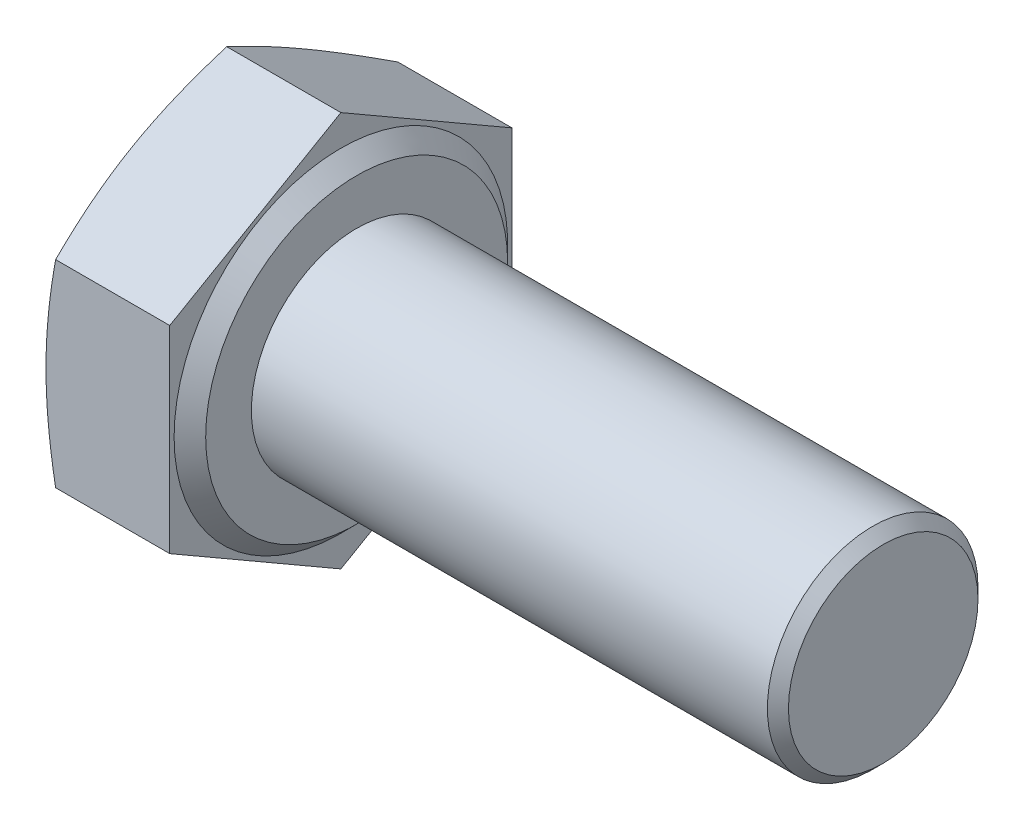
SolidWorks part; units mm, degrees
material "304 Stainless Steel"
ref_plane "Front" through (0, 0, 0) normal (0, 0, 1) x (1, 0, 0)
ref_plane "Top" through (0, 0, 0) normal (0, 1, 0) x (1, 0, 0)
ref_plane "Right" through (0, 0, 0) normal (1, 0, 0) x (0, 0, -1)
sketch "Sketch2" plane through (0, 0, 0) normal (1, 0, 0) x (0, 0, -1)
  line L1 (0, -7.5056) -> (6.5, -3.7528)
  line L2 (6.5, -3.7528) -> (6.5, 3.7528)
  line L3 (6.5, 3.7528) -> (0, 7.5056)
  line L4 (0, 7.5056) -> (-6.5, 3.7528)
  line L5 (-6.5, 3.7528) -> (-6.5, -3.7528)
  line L6 (-6.5, -3.7528) -> (0, -7.5056)
  circle A0 centre (0, 0) radius 6.5 construction
  dimension "s" = 13
extrude "BaseHead" add sketch "Sketch2" along normal blind 5.3
sketch "Sketch3" plane through (0, 0, 0) normal (0, 0, 1) x (1, 0, 0)
  line L0 (5.3, 7.5056) -> (5.3, 5.735)
  line L2 (5.3, 5.735) -> (4.7, 6.335)
  line L3 (4.7, 6.335) -> (4.7, 7.5056)
  line L5 (4.7, 7.5056) -> (5.3, 7.5056)
  line L6 (-0.9571, 0) -> (7.6478, 0) construction
  line L7 (5.3, 7.5056) -> (0, 7.5056) construction
  dimension "D1" = 45
  dimension "c" = 0.6
  dimension "dw" = 11.47
revolve "BearingFace" cut sketch "Sketch3" angle 360 about L6
sketch "Sketch4" plane through (0, 0, 0) normal (0, 0, 1) x (1, 0, 0)
  line L0 (-0.4935, 0) -> (3.5626, 0) construction
  line L2 (0, 7.5056) -> (0.366, 7.5056)
  line L4 (0.366, 7.5056) -> (0, 6.5)
  line L6 (0, 6.5) -> (0, 7.5056)
  line L7 (4.7, 7.5056) -> (0, 7.5056) construction
  dimension "D1" = 20
  dimension "D2" = 13
revolve "HeadChamfer" cut sketch "Sketch4" angle 360 about L0
sketch "Sketch5" plane through (5.3, 0, 0) normal (1, 0, 0) x (0, 0, -1)
  circle A0 centre (0, 0) radius 4
  dimension "d" = 8
extrude "BaseBody" add sketch "Sketch5" along normal blind 20
cosmetic thread "ThreadCosmetic1" [suppressed] parameters "D2"=6.647
chamfer "Chamfer1" distance 0.4 angle 45 1 edges at (25.3, 0, -4)
fillet "HeadFillet" [suppressed] radius 0.4
sketch "Sketch6" [suppressed] plane through (0, 0, 0) normal (0, 0, 1) x (1, 0, 0)
  line L0 (5.3, 4.5) -> (5.8, 4.5)
  line L1 (5.8, 4.5) -> (5.8, 4)
  line L2 (5.8, 4) -> (5.55, 3.567)
  line L3 (5.55, 3.567) -> (5.3, 4)
  line L4 (5.3, 4) -> (5.3, 4.5)
  line L5 (5.3, -5.815) -> (5.3, 5.815) construction
  line L6 (39.9, 4) -> (5.3, 4) construction
  dimension "D1" = 0.6765
revolve "Cut-Revolve10" [suppressed] cut sketch "Sketch6" angle 360
pattern_linear "LPattern10" [suppressed] count 24
equation "\"D2@Sketch4\" = \"s@Sketch2\""
equation "\"D1@Chamfer1\" = 0.05 * \"d@Sketch5\""
equation "\"D1@Sketch6\" =  ( \"d@Sketch5\" - \"D2@ThreadCosmetic1\" )  / 2"
equation "\"pitch@LPattern10\" = 1.2 * \"D1@Sketch6\""
equation "\"D1@LPattern10\" = (  \"l@BaseBody\"-\"D1@Chamfer1\" )  / \"pitch@LPattern10\""
